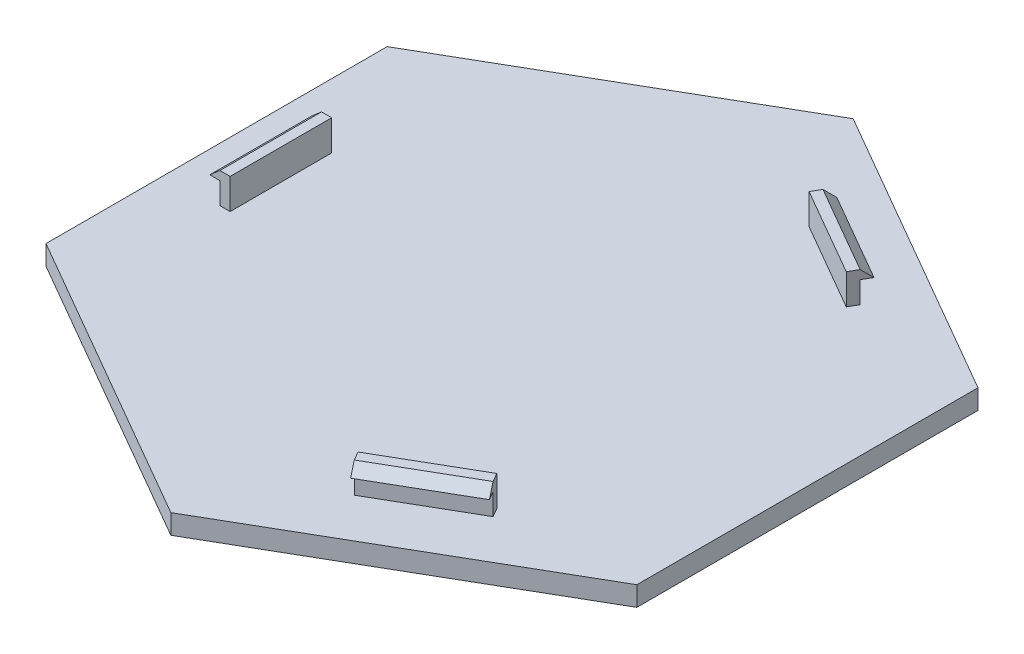
SolidWorks part; units mm, degrees
ref_plane "Plano frontal" through (0, 0, 0) normal (0, 0, 1) x (1, 0, 0)
ref_plane "Plano superior" through (0, 0, 0) normal (0, 1, 0) x (1, 0, 0)
ref_plane "Plano direito" through (0, 0, 0) normal (1, 0, 0) x (0, 0, -1)
sketch "Esboço1" plane through (0, 0, 0) normal (0, 1, 0) x (1, 0, 0)
  line L5 (-43.62, 11.0681) -> (-43.62, 25.184)
  line L6 (-43.62, 11.0681) -> (-43.62, -25.184)
  line L17 (31.3952, 32.242) -> (43.62, 25.184)
  line L18 (31.3952, 32.242) -> (0, 50.368)
  line L29 (-31.3952, -32.242) -> (-43.62, -25.184)
  line L30 (-31.3952, -32.242) -> (0, -50.368)
  line L41 (-12.2248, 43.3101) -> (0, 50.368)
  line L42 (-12.2248, 43.3101) -> (-43.62, 25.184)
  line L53 (12.2248, -43.3101) -> (0, -50.368)
  line L54 (12.2248, -43.3101) -> (43.62, -25.184)
  line L65 (43.62, -11.0681) -> (43.62, -25.184)
  line L66 (43.62, -11.0681) -> (43.62, 25.184)
extrude "Ressalto-extrusão1" add sketch "Esboço1" along normal blind 2.9
sketch "Esboço4" plane through (0, 2.9, 0) normal (0, 1, 0) x (1, 0, 0)
  line L0 (-34.12, 0) -> (-34.12, 7.5)
  line L1 (-35.62, 7.5) -> (-34.12, 7.5)
  line L3 (17.06, -29.5488) -> (10.5648, -33.2988)
  line L4 (11.3148, -34.5978) -> (10.5648, -33.2988)
  line L6 (17.06, -29.5488) -> (23.5552, -25.7988)
  line L7 (-34.12, 0) -> (-34.12, -7.5)
  line L8 (-34.12, -7.5) -> (-35.62, -7.5)
  line L9 (-35.62, 7.5) -> (-35.62, -7.5)
  line L11 (23.5552, -25.7988) -> (24.3052, -27.0978)
  line L12 (11.3148, -34.5978) -> (24.3052, -27.0978)
  line L13 (17.06, 29.5488) -> (23.5552, 25.7988)
  line L14 (24.3052, 27.0978) -> (23.5552, 25.7988)
  line L16 (17.06, 29.5488) -> (10.5648, 33.2988)
  line L17 (10.5648, 33.2988) -> (11.3148, 34.5978)
  line L18 (24.3052, 27.0978) -> (11.3148, 34.5978)
extrude "Ressalto-extrusão8" add sketch "Esboço4" along normal blind 4.5
sketch "Esboço11" plane through (-35.62, 0, 0) normal (-1, 0, 0) x (0, 0, 1)
  line L0 (-7.5, 7.4) -> (-7.5, 6.1)
  line L2 (-7.5, 7.4) -> (-7.5, 2.9) construction
  line L4 (-7.5, 6.1) -> (7.5, 6.1)
  line L5 (-7.5, 6.1) -> (-7.5, 7.4)
  line L6 (-7.5, 7.4) -> (7.5, 7.4)
  line L7 (7.5, 6.1) -> (7.5, 7.4)
extrude "Ressalto-extrusão12" add sketch "Esboço11" along normal blind 1.5
sketch "Esboço15" plane through (17.81, 0, 30.8478) normal (0.5, 0, 0.866) x (0.866, 0, -0.5)
  line L0 (-7.5, 7.4) -> (-7.5, 6.1)
  line L2 (-7.5, 6.1) -> (7.5, 6.1)
  line L3 (-7.5, 6.1) -> (-7.5, 7.4)
  line L4 (-7.5, 7.4) -> (7.5, 7.4)
  line L5 (7.5, 6.1) -> (7.5, 7.4)
  line M2 (7.5, 2.9) -> (7.5, 7.4)
  line M3 (7.5, 7.4) -> (-7.5, 7.4)
  line M4 (-7.5, 7.4) -> (-7.5, 2.9)
extrude "Ressalto-extrusão13" add sketch "Esboço15" along normal blind 1.5 contours L2 M4 M2 M3
sketch "Esboço16" plane through (17.81, 0, -30.8478) normal (0.5, 0, -0.866) x (-0.866, 0, -0.5)
  line L0 (-7.5, 7.4) -> (-7.5, 6.1)
  line L2 (-7.5, 6.1) -> (7.5, 6.1)
  line L3 (-7.5, 6.1) -> (-7.5, 7.4)
  line L4 (-7.5, 7.4) -> (7.5, 7.4)
  line L5 (7.5, 6.1) -> (7.5, 7.4)
  line M2 (7.5, 2.9) -> (7.5, 7.4)
  line M3 (7.5, 7.4) -> (-7.5, 7.4)
  line M4 (-7.5, 7.4) -> (-7.5, 2.9)
extrude "Ressalto-extrusão14" add sketch "Esboço16" along normal blind 1.5 contours L2 M4 M2 M3
sketch "Esboço17" plane through (-6.4952, 0, 3.75) normal (-0.866, 0, 0.5) x (0.5, 0, 0.866)
  line L2 (35.62, 7.4) -> (37.12, 6.1)
  line L3 (37.12, 6.1) -> (38.5228, 5.8437)
  line L4 (38.5228, 5.8437) -> (38.6597, 9.3919)
  line L5 (38.6597, 9.3919) -> (36.37, 10.1226)
  line L6 (36.37, 10.1226) -> (35.62, 7.4)
extrude "Corte-extrusão5" cut sketch "Esboço17" against normal through all
sketch "Esboço18" plane through (6.4952, 0, 3.75) normal (0.866, 0, 0.5) x (0.5, 0, -0.866)
  line L3 (35.62, 7.8923) -> (37.556, 7.8923)
  line L4 (37.556, 7.8923) -> (38.139, 7.1149)
  line L5 (38.139, 7.1149) -> (37.6856, 6.0379)
  line L6 (37.12, 6.1) -> (35.62, 7.4)
  line L7 (35.62, 7.8923) -> (35.62, 7.4)
  line L8 (37.12, 6.1) -> (37.6856, 6.0379)
extrude "Corte-extrusão8" cut sketch "Esboço18" against normal through all
sketch "Esboço19" plane through (0, 0, 7.5) normal (0, 0, 1) x (1, 0, 0)
  line L0 (-35.62, 8.4164) -> (-35.62, 7.4)
  line L1 (-35.62, 8.4164) -> (-38.576, 7.7422)
  line L2 (-38.576, 7.7422) -> (-38.2678, 5.8638)
  line L3 (-38.2678, 5.8638) -> (-37.5261, 5.4785)
  line L4 (-37.5261, 5.4785) -> (-37.12, 6.1)
  line L5 (-37.12, 6.1) -> (-35.62, 7.4)
  line L6 (-37.12, 7.4) -> (-34.12, 7.4) construction
extrude "Corte-extrusão9" cut sketch "Esboço19" against normal through all
